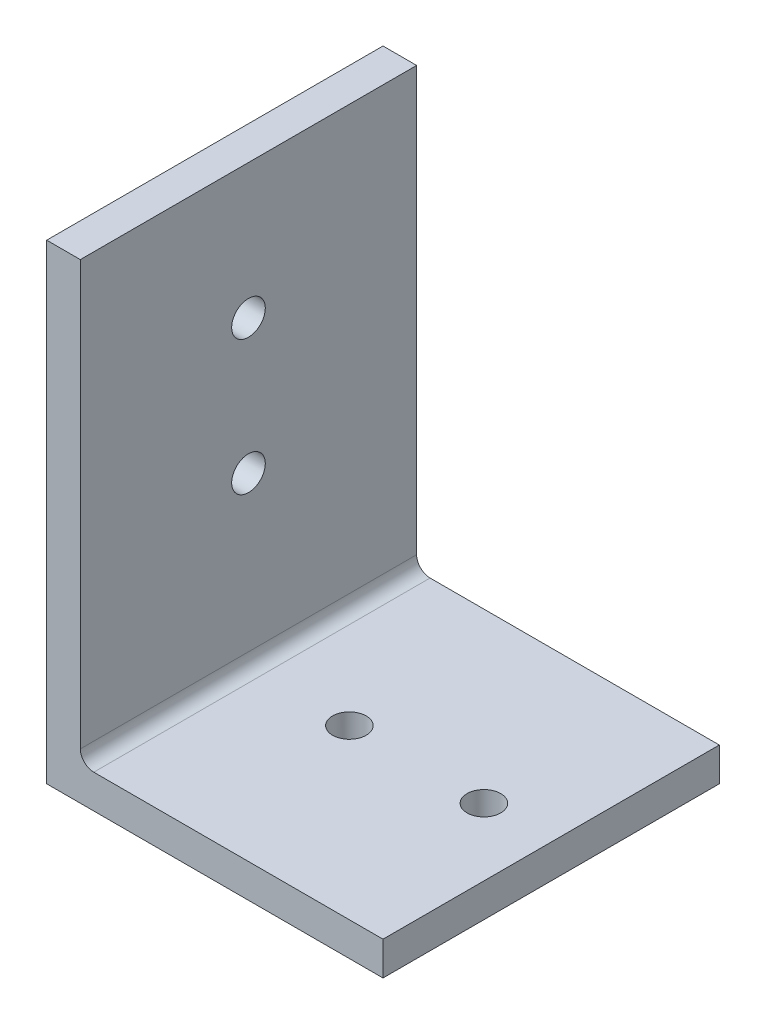
SolidWorks part; units mm, degrees
material "1023 Carbon Steel Sheet (SS)"
ref_plane "Front Plane" through (0, 0, 0) normal (0, 0, 1) x (1, 0, 0)
ref_plane "Top Plane" through (0, 0, 0) normal (0, 1, 0) x (1, 0, 0)
ref_plane "Right Plane" through (0, 0, 0) normal (1, 0, 0) x (0, 0, -1)
sketch "Sketch1" plane through (0, 0, 0) normal (0, 0, 1) x (1, 0, 0)
  line L0 (0, 0) -> (0, 88.9)
  line L1 (0, 88.9) -> (6.35, 88.9)
  line L2 (6.35, 88.9) -> (6.35, 6.35)
  line L3 (6.35, 6.35) -> (63.5, 6.35)
  line L4 (63.5, 6.35) -> (63.5, 0)
  line L5 (63.5, 0) -> (0, 0)
  dimension "D1" = 6.35
  dimension "D2" = 6.35
  dimension "D3" = 88.9
  dimension "D4" = 63.5
extrude "Boss-Extrude2" add sketch "Sketch1" along normal mid plane 63.5
sketch "Sketch2" plane through (0, 0, 0) normal (-1, 0, 0) x (0, 0, 1)
  line L0 (31.75, 88.9) -> (-31.75, 88.9) construction
  circle A0 centre (0, 63.5) radius 3.175
  circle A1 centre (0, 38.1) radius 3.175
  dimension "D1" = 6.35
  dimension "D2" = 25.4
  dimension "D3" = 25.4
extrude "Cut-Extrude1" cut sketch "Sketch2" against normal up to next
sketch "Sketch3" plane through (0, 0, 0) normal (0, -1, 0) x (1, 0, 0)
  line L0 (63.5, 31.75) -> (63.5, -31.75) construction
  circle A0 centre (25.4, 0) radius 3.175
  circle A1 centre (50.8, 0) radius 3.175
  dimension "D1" = 6.35
  dimension "D2" = 12.7
  dimension "D3" = 25.4
extrude "Cut-Extrude2" cut sketch "Sketch3" against normal up to next
fillet "Fillet2" radius 2.54 1 edges at (6.35, 6.35, 0)
